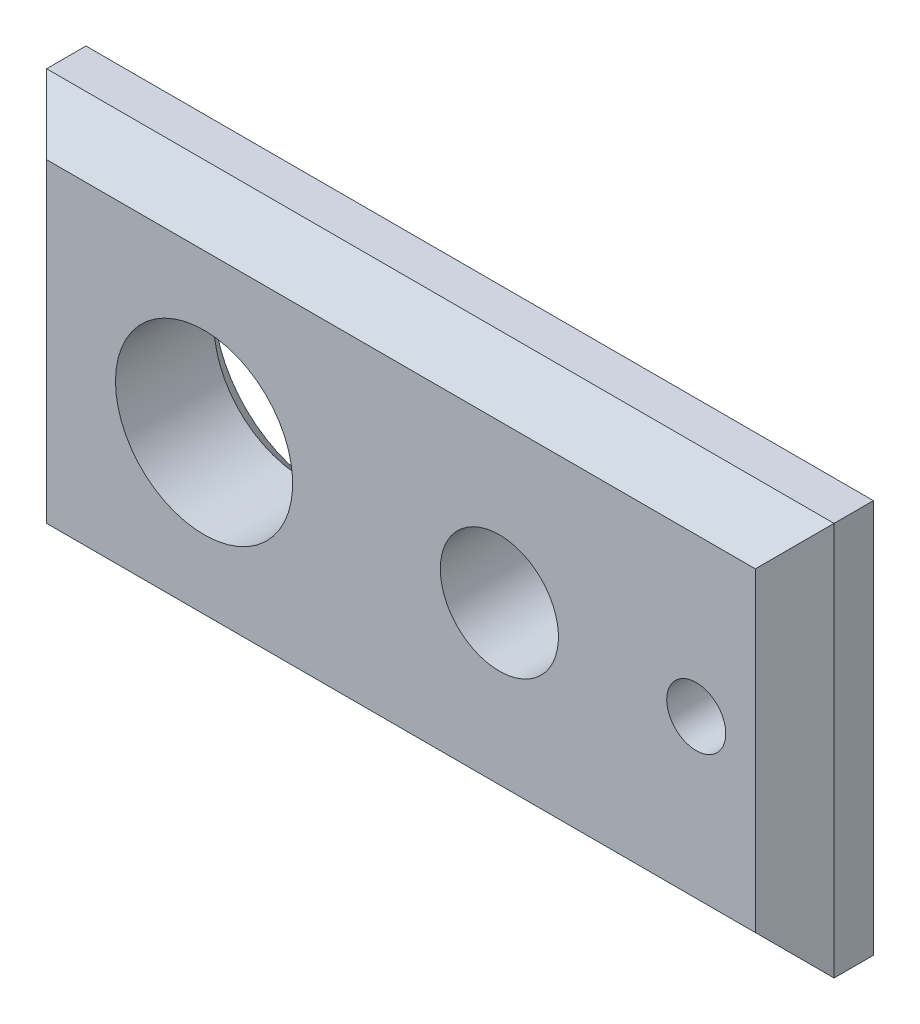
SolidWorks part; units mm, degrees
ref_plane "Plan de face" through (0, 0, 0) normal (0, 0, 1) x (1, 0, 0)
ref_plane "Plan de dessus" through (0, 0, 0) normal (0, 1, 0) x (1, 0, 0)
ref_plane "Plan de droite" through (0, 0, 0) normal (1, 0, 0) x (0, 0, -1)
sketch "Esquisse1" plane through (0, 0, 0) normal (0, 0, 1) x (1, 0, 0)
  line L1 (-1000, -500) -> (1000, -500)
  line L2 (-1000, -500) -> (-1000, 500)
  line L3 (-1000, 500) -> (1000, 500)
  line L4 (1000, -500) -> (1000, 500)
  line L5 (-1000, -500) -> (1000, 500) construction
  line L6 (-1000, 500) -> (1000, -500) construction
  point P0 (0, 0)
  point P6 (0, 0)
  dimension "D1" = 2000
  dimension "D2" = 500
extrude "Boss.-Extru.1" add sketch "Esquisse1" along normal blind 300
chamfer "Chanfrein1" distance 100 angle 45 8 edges at (-1000, 0, 0) (0, -500, 0) (1000, 0, 0) (0, 500, 0) (-1000, 0, 300) (0, -500, 300) (1000, 0, 300) (0, 500, 300)
sketch "Esquisse2" plane through (0, 0, 0) normal (0, 0, -1) x (-1, 0, 0)
  line L1 (-1000, -500) -> (-1000, 500) construction
  line L2 (-1000, 500) -> (1000, 500) construction
  circle A0 centre (-750, 0) radius 75
  circle A2 centre (500, 0) radius 225
  circle A3 centre (-250, 0) radius 150
  point P9 (0, 0)
  point P10 (0, 0)
  point P11 (0, 0)
  dimension "D1" = 150
  dimension "D2" = 500
  dimension "D3" = 450
  dimension "D5" = 750
  dimension "D9" = 300
  dimension "D4" = 250
  dimension "D6" = 500
  dimension "D7" = 500
  dimension "D8" = 500
extrude "Enlèv. mat.-Extru.1" cut sketch "Esquisse2" against normal through all
chamfer "Chanfrein2" distance 50 angle 45 3 edges at (100, 0, 0) (-725, 0, 0) (675, 0, 0)
